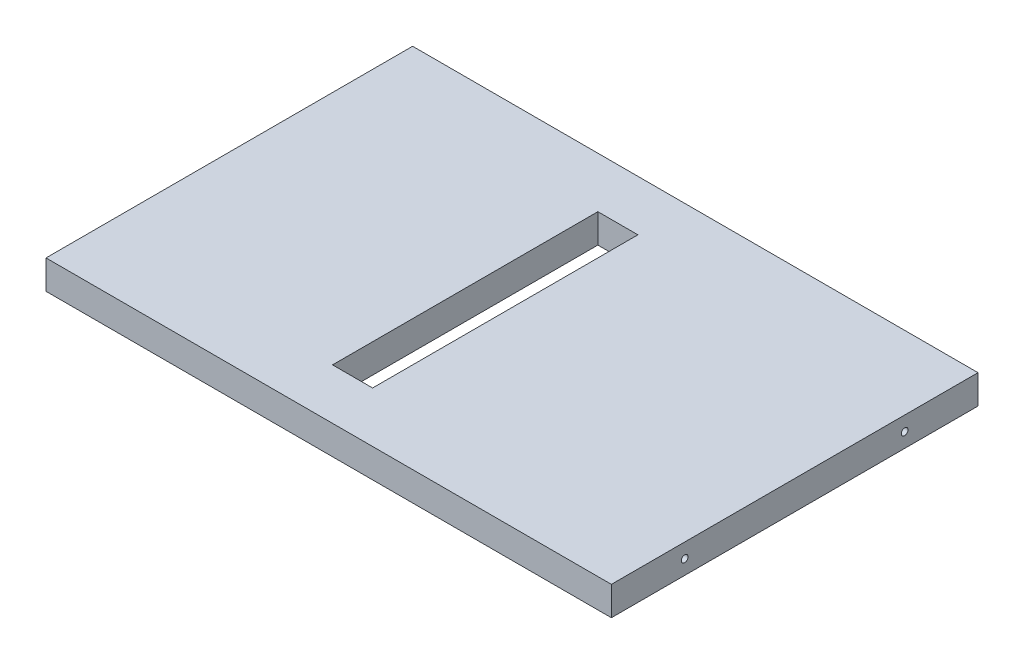
SolidWorks part; units mm, degrees
ref_plane "前视基准面" through (0, 0, 0) normal (0, 0, 1) x (1, 0, 0)
ref_plane "上视基准面" through (0, 0, 0) normal (0, 1, 0) x (1, 0, 0)
ref_plane "右视基准面" through (0, 0, 0) normal (1, 0, 0) x (0, 0, -1)
other "Configuration Table"
sketch "草图1" plane through (0, 0, 0) normal (0, 1, 0) x (1, 0, 0)
  line L1 (-29.3, -19) -> (29.3, -19)
  line L2 (-29.3, -19) -> (-29.3, 19)
  line L3 (-29.3, 19) -> (29.3, 19)
  line L4 (29.3, -19) -> (29.3, 19)
  line L5 (-29.3, -19) -> (29.3, 19) construction
  line L6 (-29.3, 19) -> (29.3, -19) construction
  point P0 (0, 0)
  dimension "D1" = 58.6
  dimension "D5" = 38
extrude "凸台-拉伸1" add sketch "草图1" along normal blind 3
sketch "草图2" plane through (0, 0, 0) normal (0, -1, 0) x (1, 0, 0)
  line L1 (-0.7, 13.75) -> (-4.85, 13.75)
  line L2 (-0.7, 13.75) -> (-0.7, -13.75)
  line L3 (-0.7, -13.75) -> (-4.85, -13.75)
  line L4 (-4.85, 13.75) -> (-4.85, -13.75)
  line L6 (29.3, 19) -> (29.3, -19) construction
  line L7 (-0.7, 13.75) -> (-0.7, 19) construction
  line L8 (-29.3, 19) -> (29.3, 19) construction
  line L9 (-0.7, -13.75) -> (-0.7, -19) construction
  line L10 (-29.3, -19) -> (29.3, -19) construction
  dimension "D1" = 27.5
  dimension "D3" = 30
  dimension "D4" = 4.15
extrude "切除-拉伸1" cut sketch "草图2" against normal through all
sketch "草图3" plane through (29.3, 0, 0) normal (1, 0, 0) x (0, 0, -1)
  circle A0 centre (-11.4, 1.5) radius 0.35
  circle A1 centre (11.4, 1.5) radius 0.35
  point P4 (0, 0)
  dimension "D1" = 0.7
extrude "切除-拉伸2" cut sketch "草图3" against normal blind 3
